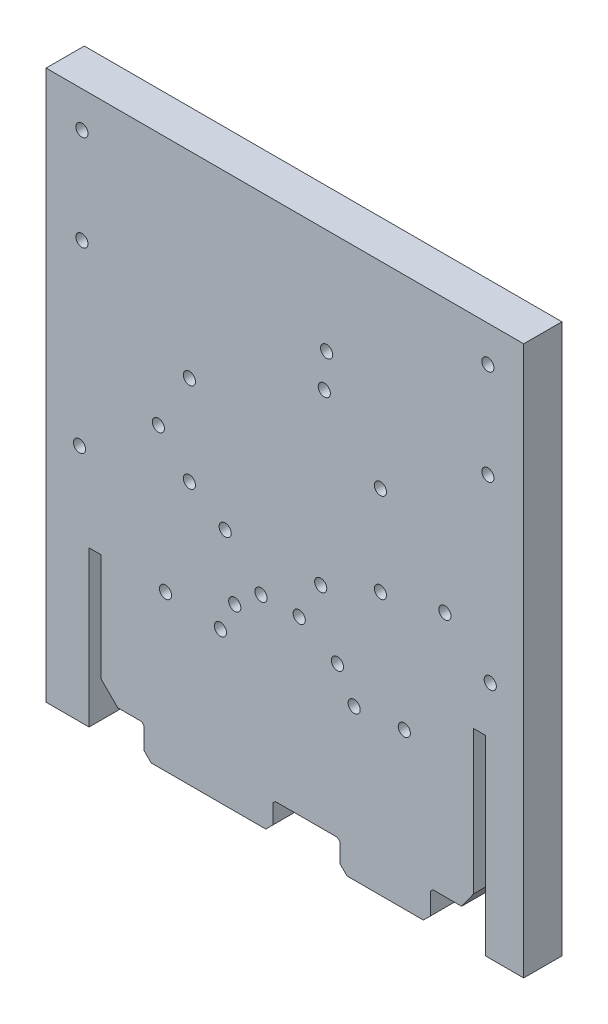
SolidWorks part; units mm, degrees
ref_plane "Front Plane" through (0, 0, 0) normal (0, 0, 1) x (1, 0, 0)
ref_plane "Top Plane" through (0, 0, 0) normal (0, 1, 0) x (1, 0, 0)
ref_plane "Right Plane" through (0, 0, 0) normal (1, 0, 0) x (0, 0, -1)
ref_plane "Dielectric_Layer Layer 1" through (0, 0, 0.8) normal (0, 0, 1) x (1, 0, 0)
sketch "Sketch1" plane through (0, 0, 0) normal (0, 0, 1) x (1, 0, 0)
  line L0 (10, 0) -> (10, 11.5)
  line L1 (10, 11.5) -> (0, 11.5)
  line L2 (0, 11.5) -> (0, 0)
  line L3 (0, 0) -> (0.9, 0)
  line L4 (0.9, 0) -> (0.9, 3.25)
  line L5 (0.9, 3.25) -> (1.15, 3.25)
  line L6 (1.15, 3.25) -> (1.15, 1)
  line L7 (1.15, 1) -> (1.5, 0.65)
  line L8 (1.5, 0.65) -> (2, 0.65)
  line L9 (2, 0.65) -> (2.05, 0.6)
  line L10 (2.05, 0.6) -> (2.05, 0.15)
  line L11 (2.05, 0.15) -> (2.2, 0)
  line L12 (2.2, 0) -> (4.6, 0)
  line L13 (4.6, 0) -> (4.75, 0.15)
  line L14 (4.75, 0.15) -> (4.75, 0.55)
  line L15 (4.75, 0.55) -> (4.8, 0.6)
  line L16 (4.8, 0.6) -> (6.1, 0.6)
  line L17 (6.1, 0.6) -> (6.15, 0.55)
  line L18 (6.15, 0.55) -> (6.15, 0.15)
  line L19 (6.15, 0.15) -> (6.3, 0)
  line L20 (6.3, 0) -> (7.9, 0)
  line L21 (7.9, 0) -> (8.05, 0.15)
  line L22 (8.05, 0.15) -> (8.05, 0.6)
  line L23 (8.05, 0.6) -> (8.1, 0.65)
  line L24 (8.1, 0.65) -> (8.7, 0.65)
  line L25 (8.7, 0.65) -> (8.95, 1)
  line L26 (8.95, 1) -> (8.95, 4)
  line L27 (8.95, 4) -> (9.2, 4)
  line L28 (9.2, 4) -> (9.2, 0)
  line L29 (9.2, 0) -> (10, 0)
extrude "Board_Outline" add sketch "Sketch1" along normal blind 0.8 separate body
sketch "Sketch2" plane through (0, 0, 0) normal (0, 0, 1) x (1, 0, 0)
  circle A0 centre (4.5, 4.2) radius 0.127
  circle A1 centre (5.875, 9.3) radius 0.127
  circle A2 centre (5.3, 4.2) radius 0.127
  circle A3 centre (5.825, 8.575) radius 0.127
  circle A4 centre (7.5, 3.25) radius 0.127
  circle A5 centre (2.5, 3.25) radius 0.127
  circle A6 centre (3.75, 5) radius 0.127
  circle A7 centre (5.75, 5) radius 0.127
  circle A8 centre (7, 5.5) radius 0.127
  circle A9 centre (3, 5.5) radius 0.127
  circle A10 centre (3, 7.375) radius 0.127
  circle A11 centre (7, 7.375) radius 0.127
  circle A12 centre (9.25, 8.75) radius 0.127
  circle A13 centre (0.75, 8.75) radius 0.127
  circle A14 centre (9.25, 10.75) radius 0.127
  circle A15 centre (0.75, 10.75) radius 0.127
  circle A16 centre (9.3, 5) radius 0.127
  circle A17 centre (0.7, 5) radius 0.127
  circle A18 centre (3.95, 3.75) radius 0.127
  circle A19 centre (8.35, 5.8) radius 0.127
  circle A20 centre (6.1, 3.75) radius 0.127
  circle A21 centre (3.65, 3.15) radius 0.127
  circle A22 centre (6.45, 3.15) radius 0.127
  circle A23 centre (2.35, 6.2) radius 0.127
extrude "NPTH" cut sketch "Sketch2" along normal through all
